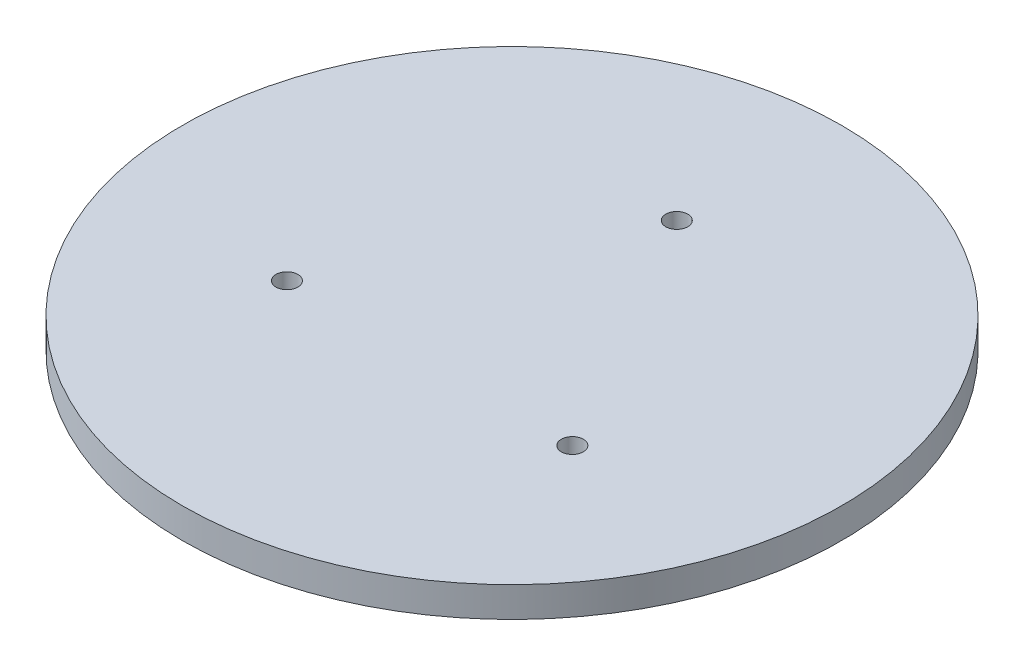
SolidWorks part; units mm, degrees
ref_plane "Front Plane" through (0, 0, 0) normal (0, 0, 1) x (1, 0, 0)
ref_plane "Top Plane" through (0, 0, 0) normal (0, 1, 0) x (1, 0, 0)
ref_plane "Right Plane" through (0, 0, 0) normal (1, 0, 0) x (0, 0, -1)
sketch "Sketch1" plane through (0, 0, 0) normal (0, 1, 0) x (1, 0, 0)
  line L0 (0, 0) -> (0, 69.342) construction
  circle A0 centre (0, 0) radius 69.342
  circle A1 centre (0, 34.671) radius 2.3114
  circle A2 centre (30.026, -17.3355) radius 2.3114
  circle A3 centre (-30.026, -17.3355) radius 2.3114
  point P13 (0, 0)
  dimension "D1" = 138.684
  dimension "D2" = 4.6228
  dimension "D3" = 3
extrude "Boss-Extrude1" add sketch "Sketch1" along normal blind 6.35
